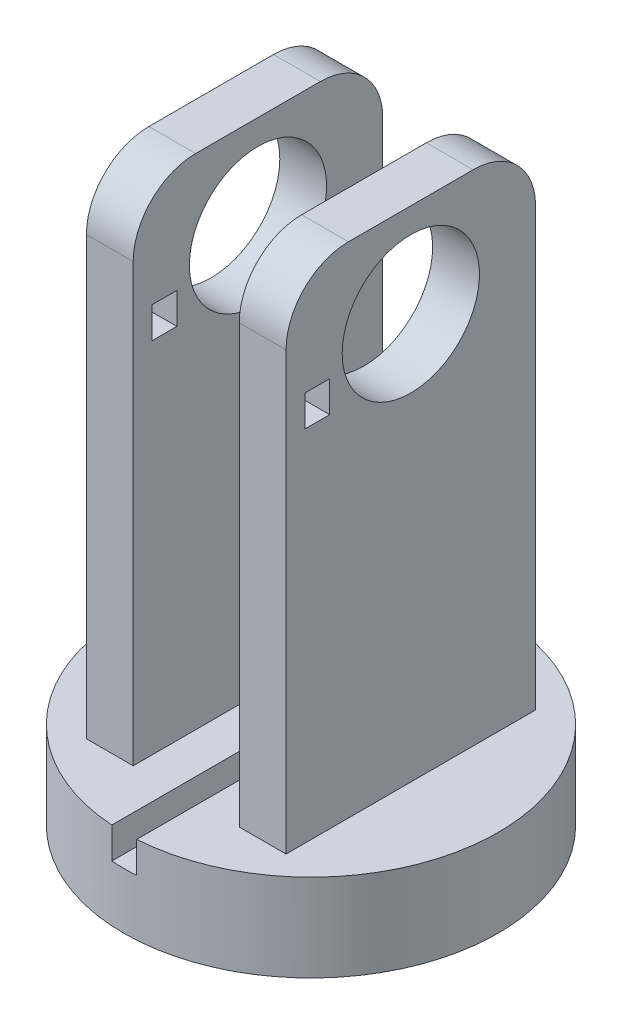
SolidWorks part; units mm, degrees
material "6061 Alloy"
ref_plane "Front Plane" through (0, 0, 0) normal (0, 0, 1) x (1, 0, 0)
ref_plane "Top Plane" through (0, 0, 0) normal (0, 1, 0) x (1, 0, 0)
ref_plane "Right Plane" through (0, 0, 0) normal (1, 0, 0) x (0, 0, -1)
sketch "Sketch1" plane through (0, 0, 0) normal (0, 1, 0) x (1, 0, 0)
  circle A0 centre (0, 0) radius 30
  dimension "D1" = 60
extrude "Boss-Extrude1" add sketch "Sketch1" along normal blind 14
sketch "Sketch2" plane through (0, 0, 0) normal (0, -1, 0) x (1, 0, 0)
  circle A0 centre (0, 0) radius 11.05
  dimension "D1" = 22.1
extrude "Cut-Extrude1" cut sketch "Sketch2" against normal blind 7
sketch "Sketch5" plane through (0, 14, 0) normal (0, 1, 0) x (1, 0, 0)
  line L0 (0, 0) -> (-8.5, 0) construction
  line L1 (0, 0) -> (8.5, 0) construction
  line L2 (-8.5, -20) -> (-8.5, 20)
  line L3 (-8.5, 20) -> (-16, 20)
  line L4 (-16, 20) -> (-16, -20)
  line L5 (-16, -20) -> (-8.5, -20)
  line L7 (16, -20) -> (16, 20)
  line L8 (16, 20) -> (8.5, 20)
  line L9 (8.5, 20) -> (8.5, -20)
  line L10 (8.5, -20) -> (16, -20)
  dimension "D1" = 8.5
  dimension "D2" = 8.5
  dimension "D3" = 7.5
  dimension "D4" = 20
  dimension "D5" = 20
  dimension "D6" = 0
  dimension "D7" = 7.5
  dimension "D8" = 20
  dimension "D9" = 20
extrude "Boss-Extrude2" add sketch "Sketch5" along normal blind 80
sketch "Sketch7" plane through (-16, 0, 0) normal (-1, 0, 0) x (0, 0, 1)
  line L0 (20, 94) -> (20, 14) construction
  line L1 (-20, 94) -> (20, 94) construction
  circle A0 centre (0, 79) radius 11
  dimension "D1" = 20
  dimension "D3" = 22
  dimension "D2" = 15
fillet "Fillet1" radius 10 4 edges at (-12.25, 94, -20) (12.25, 94, -20) (12.25, 94, 20) (-12.25, 94, 20)
extrude "Cut-Extrude3" cut sketch "Sketch7" against normal through all and the other way through all
sketch "Sketch8" plane through (0, 14, 0) normal (0, 1, 0) x (1, 0, 0)
  line L0 (0, 0) -> (2, 0) construction
  line L1 (0, 0) -> (-2, 0) construction
  line L2 (2, 29.9333) -> (2, -29.9333)
  line L3 (-2, 29.9333) -> (-2, -29.9333)
  circle A0 centre (0, 0) radius 30 construction
  arc A1 (-2, -29.9333) -> (2, -29.9333) centre (0, 0) ccw
  arc A2 (2, 29.9333) -> (-2, 29.9333) centre (0, 0) ccw
  dimension "D1" = 2
  dimension "D2" = 2
extrude "Cut-Extrude4" cut sketch "Sketch8" against normal blind 5
sketch "Sketch9" plane through (-16, 0, 0) normal (-1, 0, 0) x (0, 0, 1)
  line L2 (17, 71.5) -> (13, 71.5)
  line L3 (17, 71.5) -> (17, 76.5)
  line L4 (17, 76.5) -> (13, 76.5)
  line L5 (13, 71.5) -> (13, 76.5)
  line L6 (17, 71.5) -> (13, 76.5) construction
  line L7 (17, 76.5) -> (13, 71.5) construction
  circle A1 centre (0, 79) radius 11 construction
  point P0 (15, 74)
  dimension "D1" = 5
  dimension "D2" = 5
  dimension "D3" = 4
  dimension "D4" = 15
extrude "Cut-Extrude5" cut sketch "Sketch9" against normal up to surface (32 mm away) contours L2 L5 L4 L3 up to face at (16, 79, 11)
